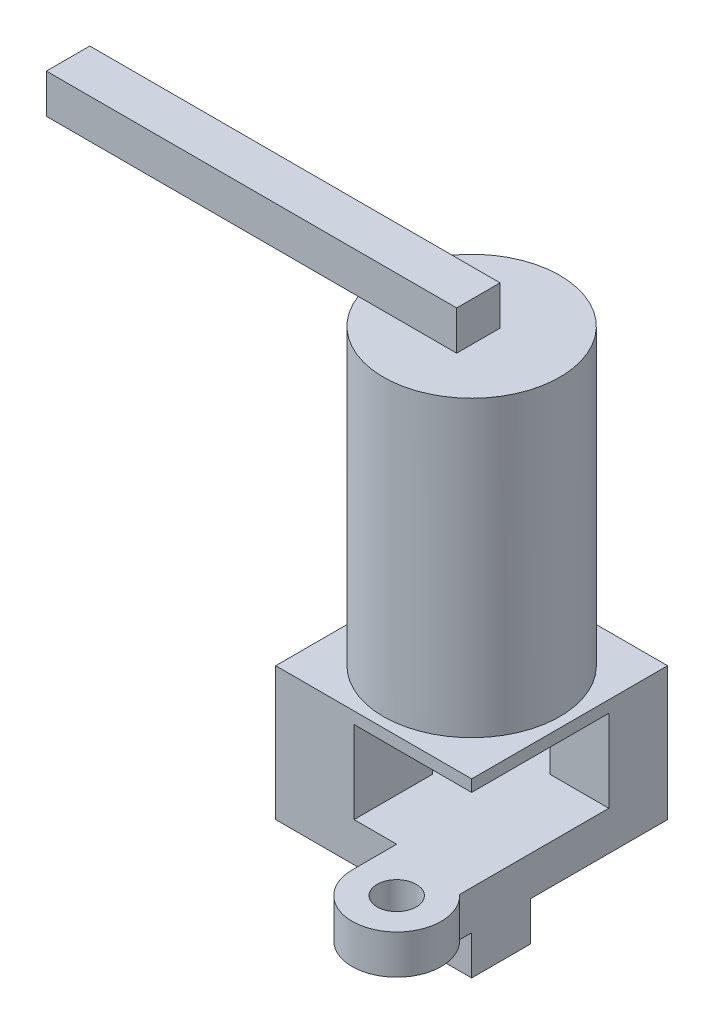
SolidWorks part; units mm, degrees
ref_plane "Front Plane" through (0, 0, 0) normal (0, 0, 1) x (1, 0, 0)
ref_plane "Top Plane" through (0, 0, 0) normal (0, 1, 0) x (1, 0, 0)
ref_plane "Right Plane" through (0, 0, 0) normal (1, 0, 0) x (0, 0, -1)
sketch "Sketch1" plane through (0, 0, 0) normal (0, 1, 0) x (1, 0, 0)
  line L1 (0, 0) -> (30.8761, 0)
  line L2 (0, 0) -> (0, 50)
  line L3 (0, 50) -> (50, 50)
  line L4 (50, 0) -> (50, 50)
  line L6 (9.8747, 47.1916) -> (24.2967, 33.2903)
  line L7 (3.4363, 40.4752) -> (17.9343, 26.6531)
  line L8 (50, 0) -> (50, -3.0636)
  line L9 (30.8761, -11.3627) -> (30.8761, 0)
  arc A2 (17.9343, 26.6531) -> (24.2967, 33.2903) centre (21.1064, 29.9804) ccw
  arc A3 (9.8747, 47.1916) -> (3.4363, 40.4752) centre (6.6463, 43.8422) ccw
  arc A5 (30.8761, -11.3627) -> (50, -3.0636) centre (42.2388, -11.3627) ccw
  circle A6 centre (42.2388, -11.3627) radius 5
  dimension "D3" = 10
  dimension "D1" = 50
  dimension "D2" = 50
extrude "Boss-Extrude1" add sketch "Sketch1" along normal blind 10
sketch "Sketch2" plane through (0, 0, 0) normal (0, -1, 0) x (1, 0, 0)
  line L3 (45, -5) -> (35, -5)
  line L4 (35, 0) -> (35, -5)
  line L7 (50, -15) -> (45, -15)
  line L8 (45, -5) -> (45, -15)
  line L20 (50, -15) -> (50, 0)
  line L21 (50, 3.0636) -> (50, -50) construction
  line L22 (50, 0) -> (35, 0)
  dimension "D3" = 10
  dimension "D4" = 10
extrude "Boss-Extrude2" add sketch "Sketch2" along normal blind 10
sketch "Sketch3" plane through (0, 10, 0) normal (0, 1, 0) x (1, 0, 0)
  line L1 (0, 0) -> (20, 0)
  line L2 (0, 0) -> (0, 20)
  line L3 (0, 20) -> (20, 20)
  line L4 (20, 0) -> (20, 20)
  line L5 (50, 50) -> (35, 50)
  line L6 (50, 50) -> (50, 35)
  line L7 (50, 35) -> (35, 35)
  line L8 (35, 50) -> (35, 35)
  dimension "D1" = 20
  dimension "D2" = 20
  dimension "D4" = 15
extrude "Boss-Extrude3" add sketch "Sketch3" along normal blind 21
sketch "Sketch4" plane through (0, 31, 0) normal (0, 1, 0) x (1, 0, 0)
  line L0 (50, 35) -> (50, 50) construction
  line L1 (0, 0) -> (50, 0)
  line L2 (0, 0) -> (0, 50)
  line L3 (0, 50) -> (50, 50)
  line L4 (50, 0) -> (50, 50)
extrude "Boss-Extrude4" add sketch "Sketch4" along normal blind 3
sketch "Sketch5" plane through (0, 34, 0) normal (0, 1, 0) x (1, 0, 0)
  line L0 (0, 0) -> (50, 0) construction
  line L1 (50, -3.0636) -> (50, 35) construction
  circle A0 centre (25, 25) radius 22.5
  dimension "D1" = 25
  dimension "D2" = 25
  dimension "D3" = 45
extrude "Boss-Extrude5" add sketch "Sketch5" along normal blind 75
sketch "Sketch6" plane through (0, 109, 0) normal (0, 1, 0) x (1, 0, 0)
  line L1 (29.0352, 17.137) -> (-75.6385, 17.137)
  line L2 (29.0352, 17.137) -> (29.0352, 28.2132)
  line L3 (29.0352, 28.2132) -> (-75.6385, 28.2132)
  line L4 (-75.6385, 17.137) -> (-75.6385, 28.2132)
extrude "Boss-Extrude6" add sketch "Sketch6" along normal blind 10
